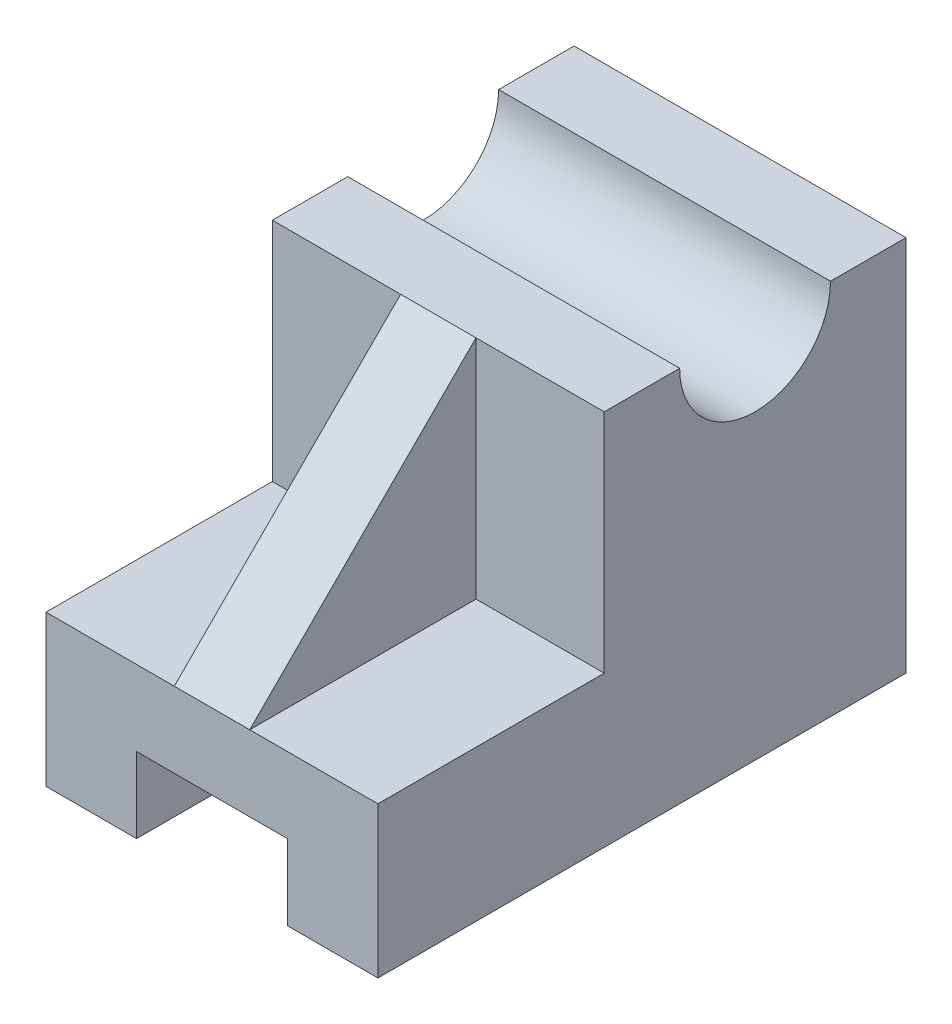
SolidWorks part; units mm, degrees
ref_plane "Front Plane" through (0, 0, 0) normal (0, 0, 1) x (1, 0, 0)
ref_plane "Top Plane" through (0, 0, 0) normal (0, 1, 0) x (1, 0, 0)
ref_plane "Right Plane" through (0, 0, 0) normal (1, 0, 0) x (0, 0, -1)
sketch "Sketch1" plane through (0, 0, 0) normal (1, 0, 0) x (0, 0, -1)
  line L0 (-18.8, -7) -> (-18.8, -27)
  line L1 (-18.8, -27) -> (51.2, -27)
  line L2 (51.2, -27) -> (51.2, 23)
  line L3 (51.2, 23) -> (11.2, 23)
  line L4 (11.2, 23) -> (11.2, -7)
  line L5 (11.2, -7) -> (-18.8, -7)
  dimension "D1" = 70
  dimension "D2" = 50
  dimension "D3" = 40
  dimension "D4" = 30
extrude "Boss-Extrude1" add sketch "Sketch1" along normal blind 44
sketch "Sketch2" plane through (44, 0, 0) normal (1, 0, 0) x (0, 0, -1)
  line L5 (51.2, 23) -> (11.2, 23) construction
  circle A0 centre (31.2, 23) radius 10
  dimension "D1" = 20
extrude "Cut-Extrude1" cut sketch "Sketch2" against normal through all
sketch "Sketch3" plane through (0, 0, 18.8) normal (0, 0, 1) x (1, 0, 0)
  line L0 (44, -27) -> (0, -27) construction
  line L1 (12, -37) -> (32, -37)
  line L2 (12, -37) -> (12, -17)
  line L3 (12, -17) -> (32, -17)
  line L4 (32, -37) -> (32, -17)
  line L5 (12, -37) -> (32, -17) construction
  line L6 (12, -17) -> (32, -37) construction
  point P0 (22, -27)
  dimension "D1" = 20
  dimension "D2" = 20
extrude "Cut-Extrude2" cut sketch "Sketch3" against normal through all
ref_plane "Plane1" through (22, 0, 0) normal (1, 0, 0) x (0, 0, -1)
sketch "Sketch4" plane through (22, 0, 0) normal (1, 0, 0) x (0, 0, -1)
  line L0 (11.2, 23) -> (-18.8, -7)
rib "Rib3" sketch "Sketch4" sketch "Sketch4" thickness 10 extrusion direction parallel to sketch draft on no parameters "D1"=10
